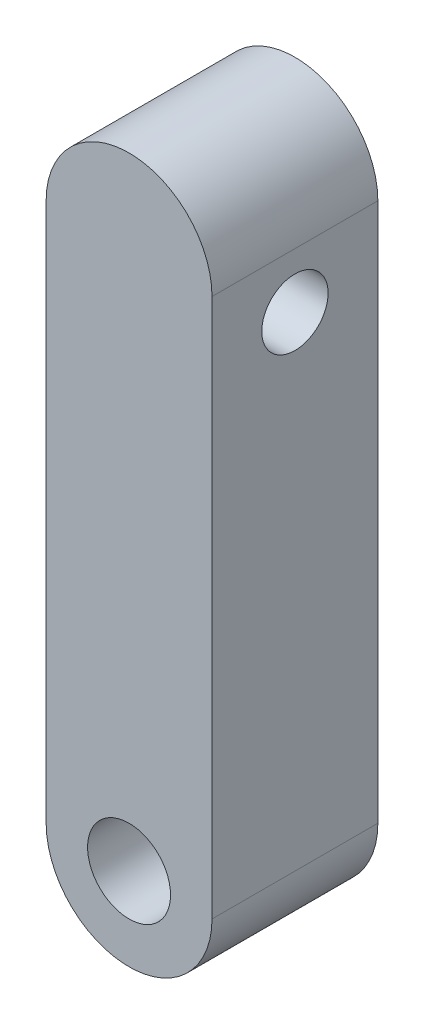
SolidWorks part; units mm, degrees
ref_plane "Front Plane" through (0, 0, 0) normal (0, 0, 1) x (1, 0, 0)
ref_plane "Top Plane" through (0, 0, 0) normal (0, 1, 0) x (1, 0, 0)
ref_plane "Right Plane" through (0, 0, 0) normal (1, 0, 0) x (0, 0, -1)
sketch "Sketch2" plane through (0, 0, 0) normal (0, 0, 1) x (1, 0, 0)
  line L0 (0, 0) -> (0, 65) construction
  line L1 (-10, 0) -> (-10, 65)
  line L2 (10, 0) -> (10, 65)
  arc A0 (-10, 0) -> (10, 0) centre (0, 0) ccw
  arc A1 (10, 65) -> (-10, 65) centre (0, 65) ccw
  circle A2 centre (0, 0) radius 5
  point P2 (0, 32.5)
  dimension "D1" = 20
  dimension "D2" = 65
extrude "Boss-Extrude1" add sketch "Sketch2" along normal blind 20
sketch "Sketch4" plane through (10, 0, 0) normal (1, 0, 0) x (0, 0, -1)
  line L0 (-10, 65) -> (-10, 58.36) construction
  line L1 (-20, 65) -> (0, 65) construction
  circle A0 centre (-10, 58.36) radius 4
  dimension "D1" = 6.64
extrude "Cut-Extrude1" cut sketch "Sketch4" against normal blind 55
ref_plane "Plane1" through (0, 0, 10) normal (0, 0, 1) x (1, 0, 0)
sketch "Sketch5" plane through (0, 0, 10) normal (0, 0, 1) x (1, 0, 0)
  line L0 (0, 0) -> (0, 16.3616) construction
  line L1 (0, 0) -> (-17.8535, 0) construction
  point P4 (0, 0)
sketch "Sketch6" plane through (0, 0, 0) normal (1, 0, 0) x (0, 0, -1)
  line L0 (-10, 0) -> (10, 0) construction
  point P4 (10, 0)
  dimension "D1" = 20
ref_plane "Plane2" through (0, 0, -10) normal (0, 0, 1) x (1, 0, 0)
sketch "Sketch7" plane through (0, 0, -10) normal (0, 0, 1) x (1, 0, 0)
  line L0 (0, 0) -> (-61.8, 0) construction
